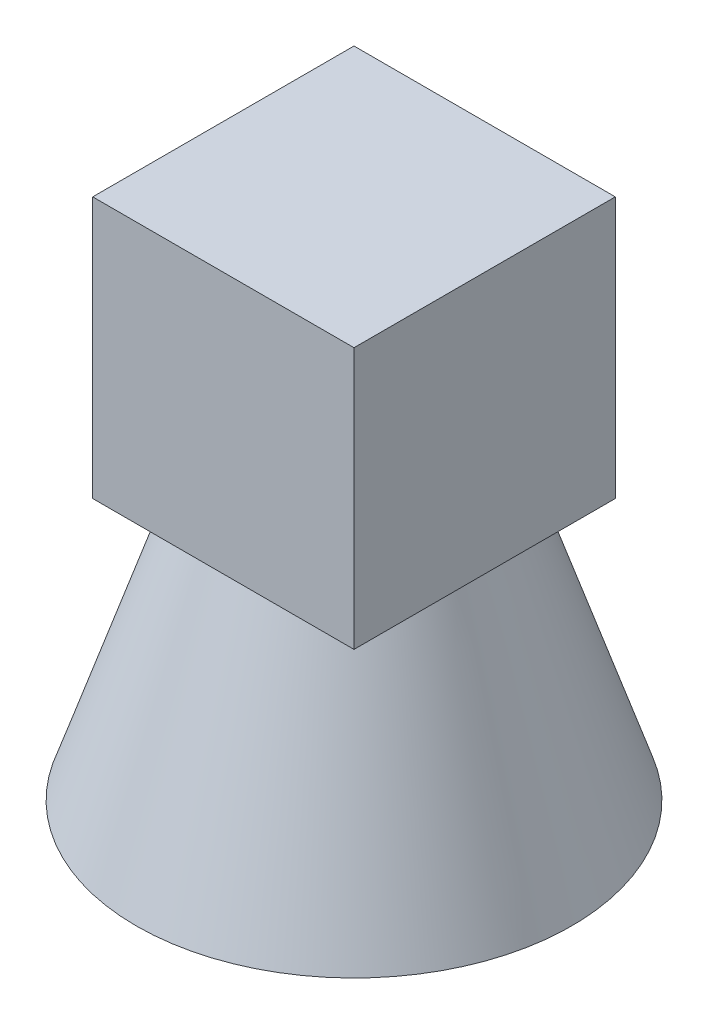
SolidWorks part; units mm, degrees
ref_plane "前视基准面" through (0, 0, 0) normal (0, 0, 1) x (1, 0, 0)
ref_plane "上视基准面" through (0, 0, 0) normal (0, 1, 0) x (1, 0, 0)
ref_plane "右视基准面" through (0, 0, 0) normal (1, 0, 0) x (0, 0, -1)
other "Configuration Table"
sketch "草图2" plane through (0, 0, 0) normal (0, 1, 0) x (1, 0, 0)
  line L1 (-15, -15) -> (15, -15)
  line L2 (-15, -15) -> (-15, 15)
  line L3 (-15, 15) -> (15, 15)
  line L4 (15, -15) -> (15, 15)
  line L5 (-15, -15) -> (15, 15) construction
  line L6 (-15, 15) -> (15, -15) construction
  point P0 (0, 0)
  dimension "D1" = 30
  dimension "D2" = 30
extrude "凸台-拉伸1" add sketch "草图2" along normal blind 30
sketch "草图3" plane through (0, 0, 0) normal (0, 0, 1) x (1, 0, 0)
  line L0 (0, 0) -> (15, 0)
  line L1 (15, 0) -> (25, -30)
  line L2 (25, -30) -> (0, -30)
  line L3 (0, -30) -> (0, 0)
  dimension "D1" = 25
  dimension "D2" = 30
revolve "旋转1" add sketch "草图3" angle 360 about L3
